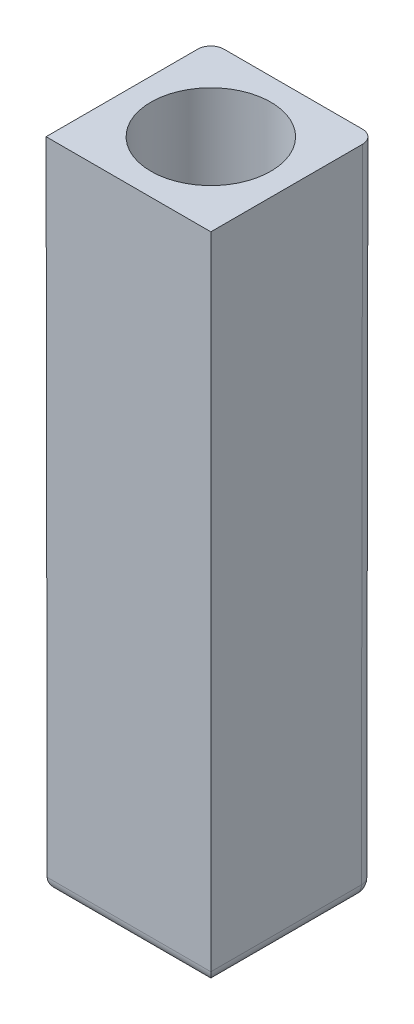
SolidWorks part; units mm, degrees
ref_plane "Front Plane" through (0, 0, 0) normal (0, 0, 1) x (1, 0, 0)
ref_plane "Top Plane" through (0, 0, 0) normal (0, 1, 0) x (1, 0, 0)
ref_plane "Right Plane" through (0, 0, 0) normal (1, 0, 0) x (0, 0, -1)
sketch "Sketch2" plane through (0, 0, 0) normal (0, 1, 0) x (1, 0, 0)
  line L1 (-12.5, 12.5) -> (12.5, 12.5)
  line L2 (-12.5, 12.5) -> (-12.5, -12.5)
  line L3 (-12.5, -12.5) -> (12.5, -12.5)
  line L4 (12.5, 12.5) -> (12.5, -12.5)
  line L5 (-12.5, 12.5) -> (12.5, -12.5) construction
  line L6 (-12.5, -12.5) -> (12.5, 12.5) construction
  circle A0 centre (0, 0) radius 9.247
  point P0 (0, 0)
  dimension "D3" = 18.494
  dimension "D1" = 25
  dimension "D2" = 25
extrude "Boss-Extrude1" add sketch "Sketch2" along normal blind 100 draft 0.05 draft outward yes
fillet "Fillet4" radius 2 6 edges at (0, 0, -12.5) (-12.5, 0, 0) (12.5, 0, 0) (0, 0, 12.5) (12.5436, 50, -12.5436) (-12.5436, 50, -12.5436)
